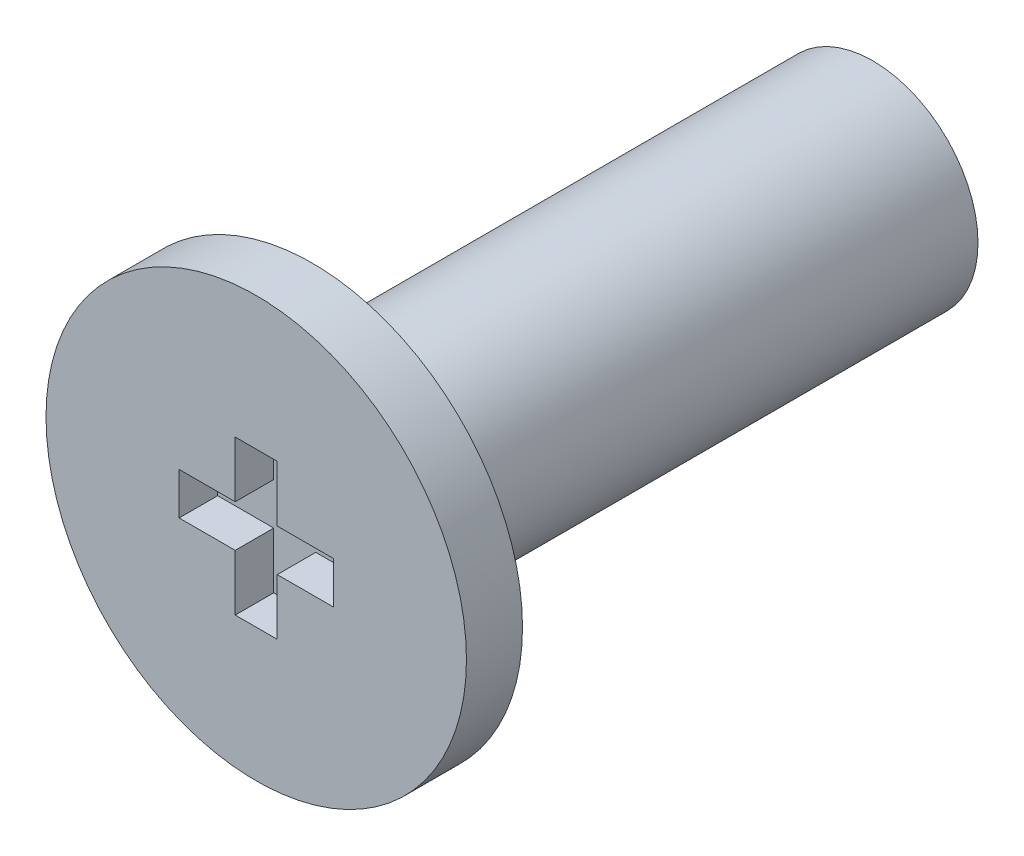
SolidWorks part; units mm, degrees
ref_plane "前视基准面" through (0, 0, 0) normal (0, 0, 1) x (1, 0, 0)
ref_plane "上视基准面" through (0, 0, 0) normal (0, 1, 0) x (1, 0, 0)
ref_plane "右视基准面" through (0, 0, 0) normal (1, 0, 0) x (0, 0, -1)
other "Configuration Table"
sketch "草图1" plane through (0, 0, 0) normal (0, 0, 1) x (1, 0, 0)
  circle A0 centre (0, 0) radius 1.5
extrude "标准杆径_头下长度" add sketch "草图1" against normal blind 8
sketch "草图2" plane through (0, 0, 0) normal (0, 0, 1) x (1, 0, 0)
  circle A0 centre (0, 0) radius 2.75
sketch "草图4" plane through (0, 0, 0) normal (0, 1, 0) x (1, 0, 0)
  line L0 (0, 0) -> (3.45, 0)
  line L1 (3.45, 0) -> (3.45, -0.3426)
  line L2 (0, -1.9) -> (0, 0)
  line L3 (0, 2) -> (0, -3.9) construction
  arc A0 (3.45, -0.3426) -> (0, -1.9) centre (0, 2.7) cw
sketch "草图5" plane through (0, 0, 0) normal (0, 0, 1) x (1, 0, 0)
  line L0 (-0.3, -1.45) -> (0.3, -1.45)
  line L1 (0.3, -1.45) -> (0.3, -0.3)
  line L2 (0.3, -0.3) -> (1.45, -0.3)
  line L3 (1.45, -0.3) -> (1.45, 0.3)
  line L4 (1.45, 0.3) -> (0.3, 0.3)
  line L5 (0.3, 0.3) -> (0.3, 1.45)
  line L6 (0.3, 1.45) -> (-0.3, 1.45)
  line L7 (-0.3, 1.45) -> (-0.3, 0.3)
  line L8 (-0.3, 0.3) -> (-1.45, 0.3)
  line L9 (-1.45, 0.3) -> (-1.45, -0.3)
  line L10 (-1.45, -0.3) -> (-0.3, -0.3)
  line L11 (-0.3, -0.3) -> (-0.3, -1.45)
sketch "草图6" plane through (0, 0, 0) normal (0, 1, 0) x (1, 0, 0)
  line L0 (0, 0) -> (3, 0)
  line L1 (3, 0) -> (3, -0.8)
  line L2 (3, -0.8) -> (0, -0.8)
  line L3 (0, -0.8) -> (0, 0)
  line L4 (0, 2) -> (0, -2.8) construction
revolve "已确认_十字槽超薄头" add sketch "草图6" angle 360 about L4
sketch "草图7" plane through (0, 0, 0) normal (0, 0, 1) x (1, 0, 0)
  line L0 (-0.3, -1.1) -> (0.3, -1.1)
  line L1 (0.3, -1.1) -> (0.3, -0.3)
  line L2 (0.3, -0.3) -> (1.1, -0.3)
  line L3 (1.1, -0.3) -> (1.1, 0.3)
  line L4 (1.1, 0.3) -> (0.3, 0.3)
  line L5 (0.3, 0.3) -> (0.3, 1.1)
  line L6 (0.3, 1.1) -> (-0.3, 1.1)
  line L7 (-0.3, 1.1) -> (-0.3, 0.3)
  line L8 (-0.3, 0.3) -> (-1.1, 0.3)
  line L9 (-1.1, 0.3) -> (-1.1, -0.3)
  line L10 (-1.1, -0.3) -> (-0.3, -0.3)
  line L11 (-0.3, -0.3) -> (-0.3, -1.1)
extrude "十字槽_PH1_简化" cut sketch "草图7" against normal blind 0.56 from offset 0.81
